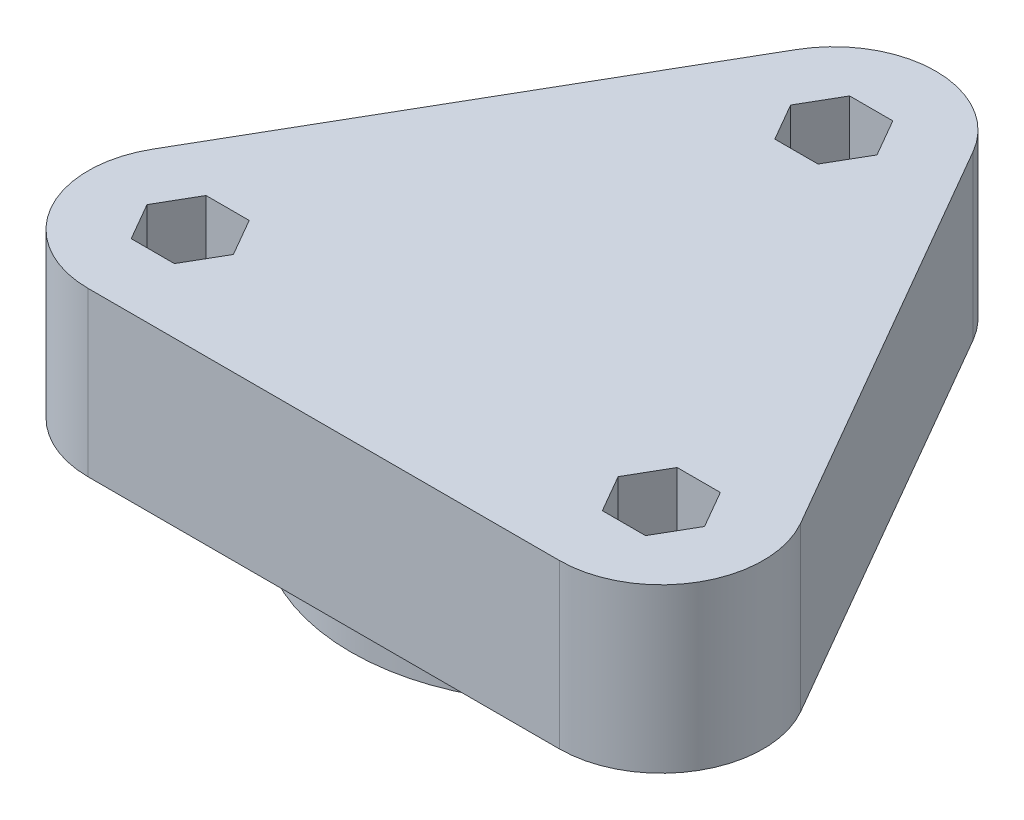
SolidWorks part; units mm, degrees
material "ABS"
ref_plane "Plan de face" through (0, 0, 0) normal (0, 0, 1) x (1, 0, 0)
ref_plane "Plan de dessus" through (0, 0, 0) normal (0, 1, 0) x (1, 0, 0)
ref_plane "Plan de droite" through (0, 0, 0) normal (1, 0, 0) x (0, 0, -1)
sketch "Esquisse1" plane through (0, 0, 0) normal (0, 1, 0) x (1, 0, 0)
  line L0 (-6.4952, 23.75) -> (-23.8157, -6.25)
  line L1 (-17.3205, -17.5) -> (17.3205, -17.5)
  line L2 (6.4952, 23.75) -> (23.8157, -6.25)
  line L3 (0, 20) -> (0, 0) construction
  line L4 (0, 0) -> (-17.3205, -10) construction
  line L6 (17.3205, -10) -> (0, 0) construction
  circle A0 centre (0, 0) radius 11.9
  circle A1 centre (-17.3205, -10) radius 1.6
  arc A2 (-23.8157, -6.25) -> (-17.3205, -17.5) centre (-17.3205, -10) ccw
  circle A3 centre (0, 20) radius 1.6
  circle A4 centre (17.3205, -10) radius 1.6
  circle A5 centre (0, 0) radius 16 construction
  arc A6 (17.3205, -17.5) -> (23.8157, -6.25) centre (17.3205, -10) ccw
  arc A7 (6.4952, 23.75) -> (-6.4952, 23.75) centre (0, 20) ccw
  circle A8 centre (0, 20) radius 4 construction
  dimension "D1" = 23.8
  dimension "D2" = 3.2
  dimension "D3" = 32
  dimension "D4" = 120
  dimension "D6" = 49.641
  dimension "D8" = 7.5
  dimension "D9" = 20
  dimension "D10" = 8
  dimension "D5" = 17.5
  dimension "D7" = 45
extrude "Boss.-Extru.1" add sketch "Esquisse1" along normal blind 12
sketch "Esquisse2" plane through (0, 12, 0) normal (0, 1, 0) x (1, 0, 0)
  line L0 (23.8157, -6.25) -> (6.4952, 23.75) construction
  line L1 (-18.9082, -7.25) -> (-20.4959, -10)
  line L2 (-20.4959, -10) -> (-18.9082, -12.75)
  line L3 (-18.9082, -12.75) -> (-15.7328, -12.75)
  line L4 (-15.7328, -12.75) -> (-14.1451, -10)
  line L5 (-14.1451, -10) -> (-15.7328, -7.25)
  line L6 (-15.7328, -7.25) -> (-18.9082, -7.25)
  line L7 (-1.5877, 22.75) -> (-3.1754, 20)
  line L8 (-3.1754, 20) -> (-1.5877, 17.25)
  line L9 (-1.5877, 17.25) -> (1.5877, 17.25)
  line L10 (1.5877, 17.25) -> (3.1754, 20)
  line L11 (3.1754, 20) -> (1.5877, 22.75)
  line L12 (1.5877, 22.75) -> (-1.5877, 22.75)
  line L13 (18.9082, -7.25) -> (15.7328, -7.25)
  line L14 (15.7328, -7.25) -> (14.1451, -10)
  line L15 (14.1451, -10) -> (15.7328, -12.75)
  line L16 (15.7328, -12.75) -> (18.9082, -12.75)
  line L17 (18.9082, -12.75) -> (20.4959, -10)
  line L18 (20.4959, -10) -> (18.9082, -7.25)
  line L19 (-6.4952, 23.75) -> (-23.8157, -6.25) construction
  circle A0 centre (-17.3205, -10) radius 2.75 construction
  circle A1 centre (0, 20) radius 2.75 construction
  circle A2 centre (17.3205, -10) radius 2.75 construction
  dimension "D1" = 5.5
extrude "Enlèv. mat.-Extru.1" cut sketch "Esquisse2" against normal blind 5
sketch "Sketch1" plane through (0, 12, 0) normal (0, 1, 0) x (1, 0, 0)
  circle A0 centre (0, 0) radius 11.9 construction
  circle A1 centre (0, 0) radius 11.9
extrude "Boss-Extrude1" add sketch "Sketch1" against normal blind 3.5
sketch "Sketch2" plane through (0, 0, 0) normal (0, -1, 0) x (1, 0, 0)
  circle A0 centre (0, 0) radius 15.5
  circle A1 centre (0, 0) radius 11.9 construction
  circle A2 centre (0, 0) radius 11.9
  dimension "D1" = 31
extrude "Boss-Extrude2" add sketch "Sketch2" along normal blind 3.5
